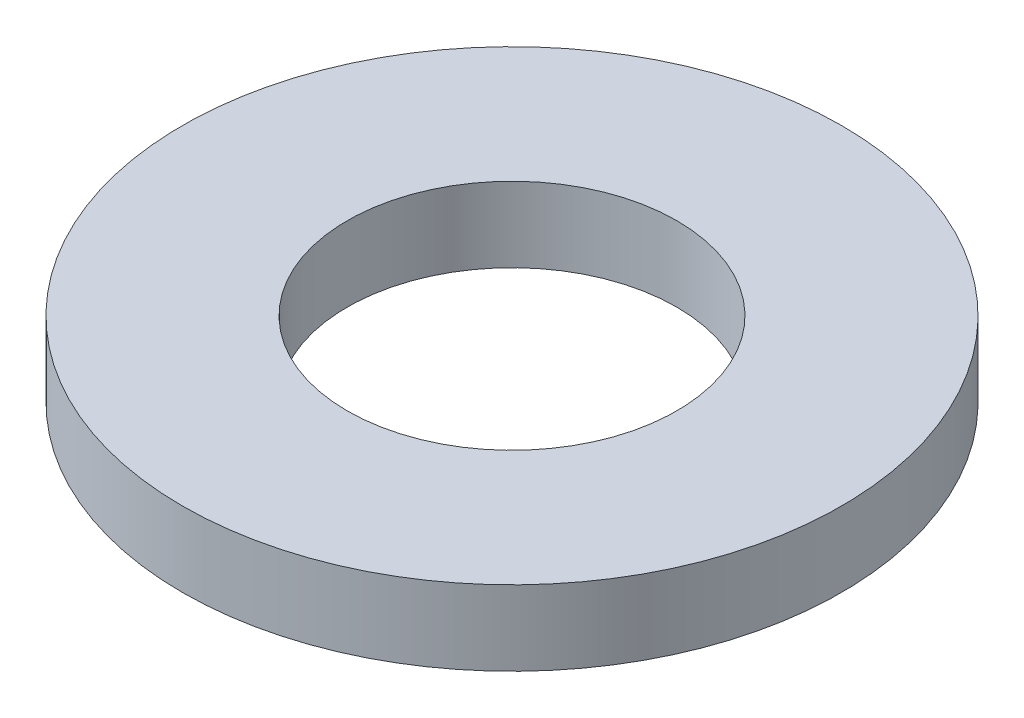
SolidWorks part; units mm, degrees
material "ASTM A36 Steel"
ref_plane "Front Plane" through (0, 0, 0) normal (0, 0, 1) x (1, 0, 0)
ref_plane "Top Plane" through (0, 0, 0) normal (0, 1, 0) x (1, 0, 0)
ref_plane "Right Plane" through (0, 0, 0) normal (1, 0, 0) x (0, 0, -1)
sketch "Sketch1" plane through (0, 0, 0) normal (0, 0, 1) x (1, 0, 0)
  line L0 (0, 168.9286) -> (0, -141.9196) construction
  line L2 (55, 12.5) -> (110, 12.5)
  line L3 (55, 12.5) -> (55, -12.5)
  line L4 (55, -12.5) -> (110, -12.5)
  line L5 (110, 12.5) -> (110, -12.5)
  line L6 (55, 12.5) -> (110, -12.5) construction
  line L7 (55, -12.5) -> (110, 12.5) construction
  point P3 (82.5, 0)
  point P8 (0, 0)
  dimension "D1" = 55
  dimension "D2" = 25
  dimension "D3" = 110
revolve "Revolve1" add sketch "Sketch1" angle 360 about L0
